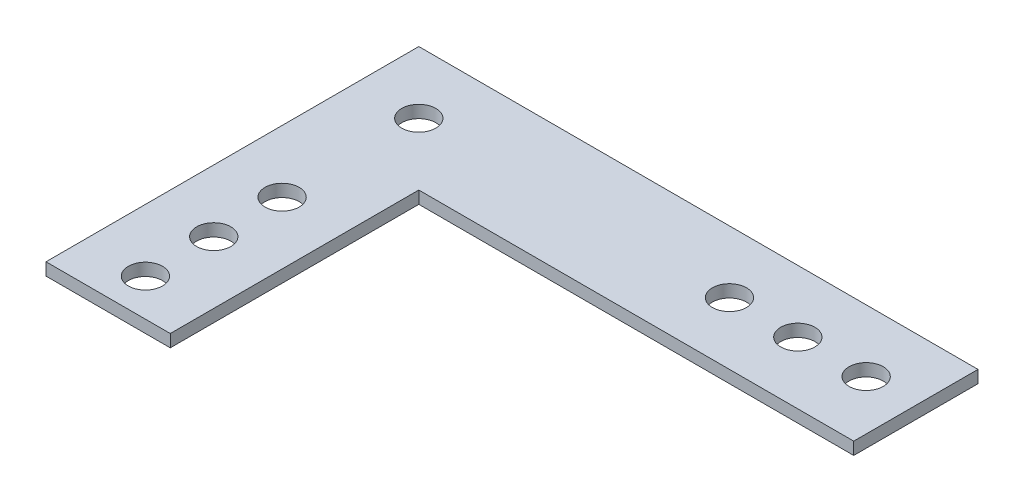
SolidWorks part; units mm, degrees
ref_plane "前视基准面" through (0, 0, 0) normal (0, 0, 1) x (1, 0, 0)
ref_plane "上视基准面" through (0, 0, 0) normal (0, 1, 0) x (1, 0, 0)
ref_plane "右视基准面" through (0, 0, 0) normal (1, 0, 0) x (0, 0, -1)
sketch "草图1" plane through (0, 0, 0) normal (0, 1, 0) x (1, 0, 0)
  line L0 (90, -10) -> (10, -10) construction
  line L1 (0, 0) -> (90, 0)
  line L2 (0, 0) -> (0, -60)
  line L3 (0, -60) -> (20, -60)
  line L4 (90, 0) -> (90, -20)
  line L5 (10, -10) -> (10, -60) construction
  line L7 (90, -20) -> (20, -20)
  line L8 (20, -60) -> (20, -20)
  circle A0 centre (10, -54) radius 2.75
  circle A1 centre (82, -10) radius 2.75
  circle A2 centre (10, -43) radius 2.75
  circle A3 centre (10, -32) radius 2.75
  circle A4 centre (71, -10) radius 2.75
  circle A5 centre (60, -10) radius 2.75
  circle A6 centre (10, -10) radius 2.75
  point P12 (10, -60)
  dimension "D5" = 5.5
  dimension "D6" = 5.5
  dimension "D1" = 60
  dimension "D2" = 90
  dimension "D3" = 20
  dimension "D4" = 20
  dimension "D7" = 6
  dimension "D8" = 8
  dimension "D9" = 11
  dimension "D10" = 11
  dimension "D11" = 11
  dimension "D12" = 11
extrude "凸台-拉伸1" add sketch "草图1" along normal blind 2
